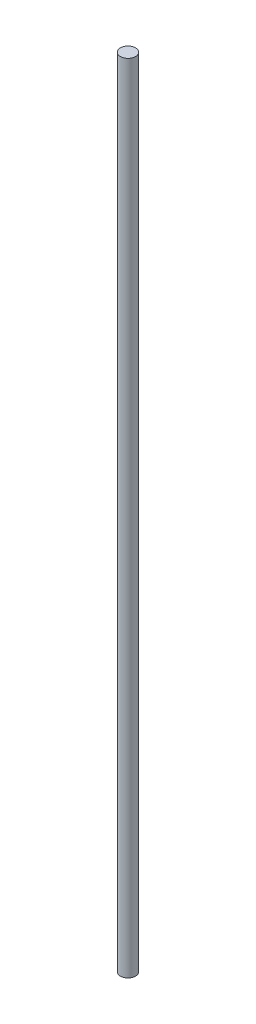
SolidWorks part; units mm, degrees
ref_plane "Front Plane" through (0, 0, 0) normal (0, 0, 1) x (1, 0, 0)
ref_plane "Top Plane" through (0, 0, 0) normal (0, 1, 0) x (1, 0, 0)
ref_plane "Right Plane" through (0, 0, 0) normal (1, 0, 0) x (0, 0, -1)
sketch "Sketch1" plane through (0, 0, 0) normal (0, 1, 0) x (1, 0, 0)
  circle A0 centre (-20.4401, 20.576) radius 2
extrude "Boss-Extrude1" add sketch "Sketch1" along normal blind 210
